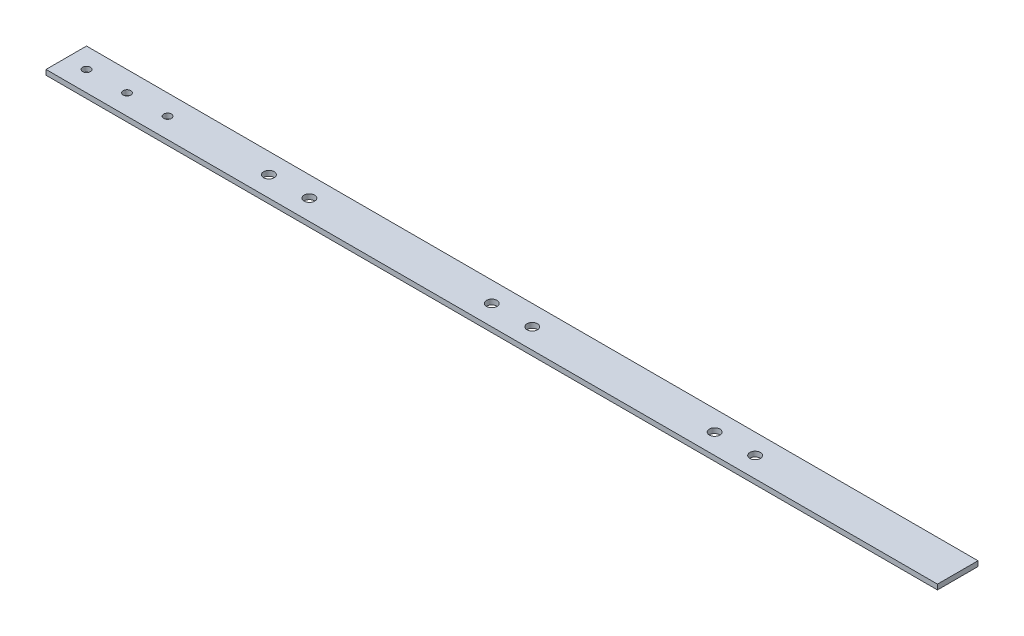
SolidWorks part; units mm, degrees
ref_plane "Front Plane" through (0, 0, 0) normal (0, 0, 1) x (1, 0, 0)
ref_plane "Top Plane" through (0, 0, 0) normal (0, 1, 0) x (1, 0, 0)
ref_plane "Right Plane" through (0, 0, 0) normal (1, 0, 0) x (0, 0, -1)
sketch "Sketch1" plane through (0, 0, 0) normal (0, 1, 0) x (1, 0, 0)
  line L1 (-279.4, 12.7) -> (279.4, 12.7)
  line L2 (-279.4, 12.7) -> (-279.4, -12.7)
  line L3 (-279.4, -12.7) -> (279.4, -12.7)
  line L4 (279.4, 12.7) -> (279.4, -12.7)
  line L5 (-279.4, 12.7) -> (279.4, -12.7) construction
  line L6 (-279.4, -12.7) -> (279.4, 12.7) construction
  point P0 (0, 0)
  dimension "D1" = 25.4
  dimension "D2" = 558.8
extrude "Boss-Extrude1" add sketch "Sketch1" along normal blind 3.175
sketch "Sketch2" plane through (0, 3.175, 0) normal (0, 1, 0) x (1, 0, 0)
  line L0 (-279.4, 12.7) -> (-279.4, -12.7) construction
  line L1 (-279.4, -12.7) -> (279.4, -12.7) construction
  circle A0 centre (-266.7, 0) radius 2.413
  circle A1 centre (-241.3, 0) radius 2.413
  circle A2 centre (-215.9, 0) radius 2.413
  point P10 (0, 0)
  point P11 (0, 0)
  dimension "D1" = 4.826
  dimension "D2" = 4.826
  dimension "D3" = 4.826
  dimension "D4" = 12.7
  dimension "D5" = 25.4
  dimension "D6" = 25.4
  dimension "D7" = 12.7
extrude "Cut-Extrude1" cut sketch "Sketch2" against normal through all
sketch "Sketch3" plane through (0, 3.175, 0) normal (0, 1, 0) x (1, 0, 0)
  line L0 (-279.4, -12.7) -> (279.4, -12.7) construction
  line L1 (-279.4, 12.7) -> (-279.4, -12.7) construction
  line L2 (279.4, -12.7) -> (279.4, 12.7) construction
  circle A0 centre (-152.4, 0) radius 3.302
  circle A1 centre (-127, 0) radius 3.302
  circle A2 centre (-12.7, 0) radius 3.302
  circle A3 centre (12.7, 0) radius 3.302
  circle A4 centre (127, 0) radius 3.302
  circle A5 centre (152.4, 0) radius 3.302
  dimension "D2" = 6.604
  dimension "D3" = 6.604
  dimension "D8" = 6.604
  dimension "D9" = 6.604
  dimension "D11" = 6.604
  dimension "D12" = 6.604
  dimension "D1" = 25.4
  dimension "D4" = 12.7
  dimension "D5" = 127
  dimension "D6" = 25.4
  dimension "D7" = 12.7
  dimension "D10" = 25.4
  dimension "D13" = 127
extrude "Cut-Extrude2" cut sketch "Sketch3" against normal through all
